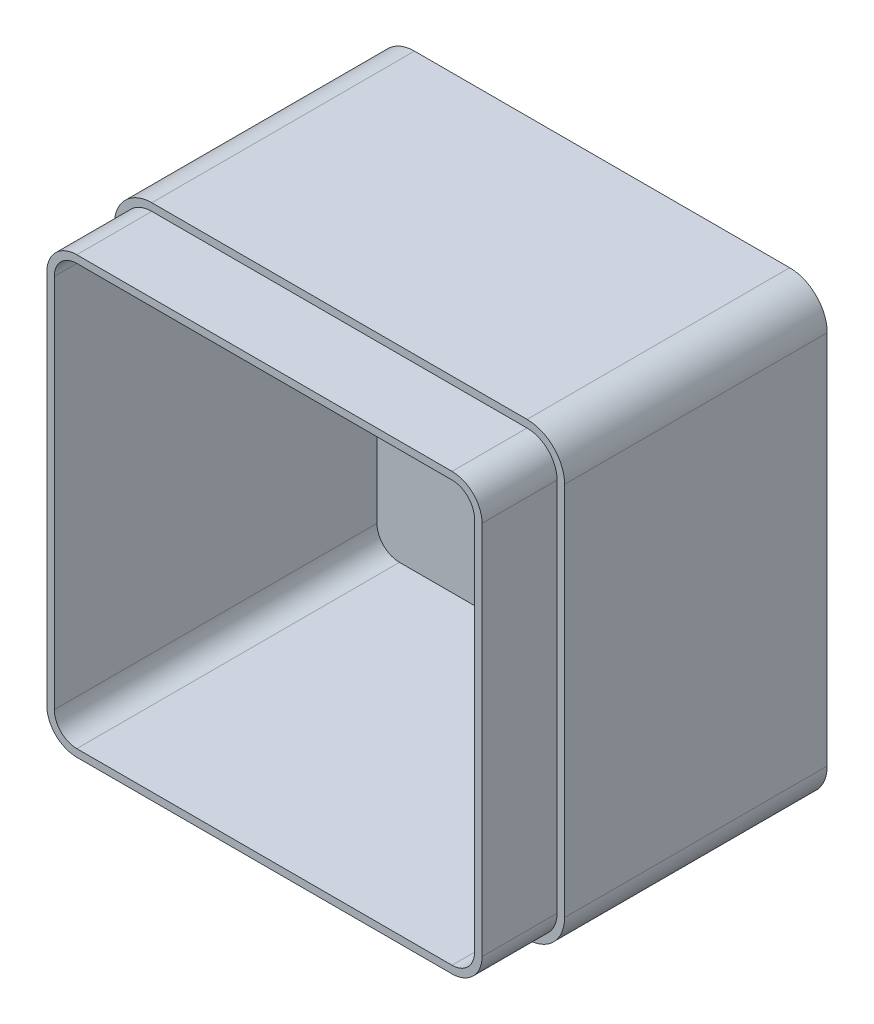
SolidWorks part; units mm, degrees
ref_plane "Front Plane" through (0, 0, 0) normal (0, 0, 1) x (1, 0, 0)
ref_plane "Top Plane" through (0, 0, 0) normal (0, 1, 0) x (1, 0, 0)
ref_plane "Right Plane" through (0, 0, 0) normal (1, 0, 0) x (0, 0, -1)
sketch "Sketch1" plane through (0, 0, 0) normal (0, 0, 1) x (1, 0, 0)
  line L1 (0, 0) -> (120, 0)
  line L2 (0, 0) -> (0, 120)
  line L3 (0, 120) -> (120, 120)
  line L4 (120, 0) -> (120, 120)
  dimension "D1" = 120
  dimension "D2" = 120
extrude "Boss-Extrude1" add sketch "Sketch1" along normal blind 90
fillet "Fillet1" radius 10 4 edges at (120, 0, 45) (0, 0, 45) (0, 120, 45) (120, 120, 45)
shell "Shell1" thickness 4
sketch "Sketch6" plane through (0, 0, 90) normal (0, 0, 1) x (1, 0, 0)
  line L0 (120, 10) -> (120, 110) construction
  line L1 (10, 0) -> (110, 0) construction
  line L2 (0, 110) -> (0, 10) construction
  line L3 (110, 120) -> (10, 120) construction
  line L4 (120, 10) -> (120, 110)
  line L5 (10, 0) -> (110, 0)
  line L6 (0, 110) -> (0, 10)
  line L7 (110, 120) -> (10, 120)
  line L12 (10, 0) -> (110, 0)
  line L13 (120, 10) -> (120, 110)
  line L14 (110, 120) -> (10, 120)
  line L15 (0, 110) -> (0, 10)
  line L16 (10, 0) -> (110, 0)
  line L17 (120, 10) -> (120, 110)
  line L18 (110, 120) -> (10, 120)
  line L19 (0, 110) -> (0, 10)
  arc A0 (110, 0) -> (120, 10) centre (110, 10) ccw construction
  arc A1 (0, 10) -> (10, 0) centre (10, 10) ccw construction
  arc A2 (10, 120) -> (0, 110) centre (10, 110) ccw construction
  arc A3 (120, 110) -> (110, 120) centre (110, 110) ccw construction
  arc A4 (110, 0) -> (120, 10) centre (110, 10) ccw
  arc A5 (0, 10) -> (10, 0) centre (10, 10) ccw
  arc A6 (10, 120) -> (0, 110) centre (10, 110) ccw
  arc A7 (120, 110) -> (110, 120) centre (110, 110) ccw
  arc A12 (110, 0) -> (120, 10) centre (110, 10) ccw
  arc A13 (120, 110) -> (110, 120) centre (110, 110) ccw
  arc A14 (10, 120) -> (0, 110) centre (10, 110) ccw
  arc A15 (0, 10) -> (10, 0) centre (10, 10) ccw
  arc A16 (110, 0) -> (120, 10) centre (110, 10) ccw
  arc A17 (120, 110) -> (110, 120) centre (110, 110) ccw
  arc A18 (10, 120) -> (0, 110) centre (10, 110) ccw
  arc A19 (0, 10) -> (10, 0) centre (10, 10) ccw
  dimension "D1" = 0
sketch "Sketch8" plane through (0, 0, 90) normal (0, 0, 1) x (1, 0, 0)
  line L0 (10, 0) -> (110, 0) construction
  line L1 (0, 110) -> (0, 10) construction
  line L2 (110, 120) -> (10, 120) construction
  line L3 (120, 10) -> (120, 110) construction
  line L4 (10, 0) -> (110, 0)
  line L5 (0, 110) -> (0, 10)
  line L6 (110, 120) -> (10, 120)
  line L7 (120, 10) -> (120, 110)
  line L8 (2, 110) -> (2, 10)
  line L9 (10, 2) -> (110, 2)
  line L10 (118, 10) -> (118, 110)
  line L11 (110, 118) -> (10, 118)
  arc A0 (0, 10) -> (10, 0) centre (10, 10) ccw construction
  arc A1 (10, 120) -> (0, 110) centre (10, 110) ccw construction
  arc A2 (120, 110) -> (110, 120) centre (110, 110) ccw construction
  arc A3 (110, 0) -> (120, 10) centre (110, 10) ccw construction
  arc A4 (0, 10) -> (10, 0) centre (10, 10) ccw
  arc A5 (10, 120) -> (0, 110) centre (10, 110) ccw
  arc A6 (120, 110) -> (110, 120) centre (110, 110) ccw
  arc A7 (110, 0) -> (120, 10) centre (110, 10) ccw
  arc A8 (2, 10) -> (10, 2) centre (10, 10) ccw
  arc A9 (110, 2) -> (118, 10) centre (110, 10) ccw
  arc A10 (118, 110) -> (110, 118) centre (110, 110) ccw
  arc A11 (10, 118) -> (2, 110) centre (10, 110) ccw
  dimension "D1" = 2
extrude "Cut-Extrude1" cut sketch "Sketch8" against normal blind 20
